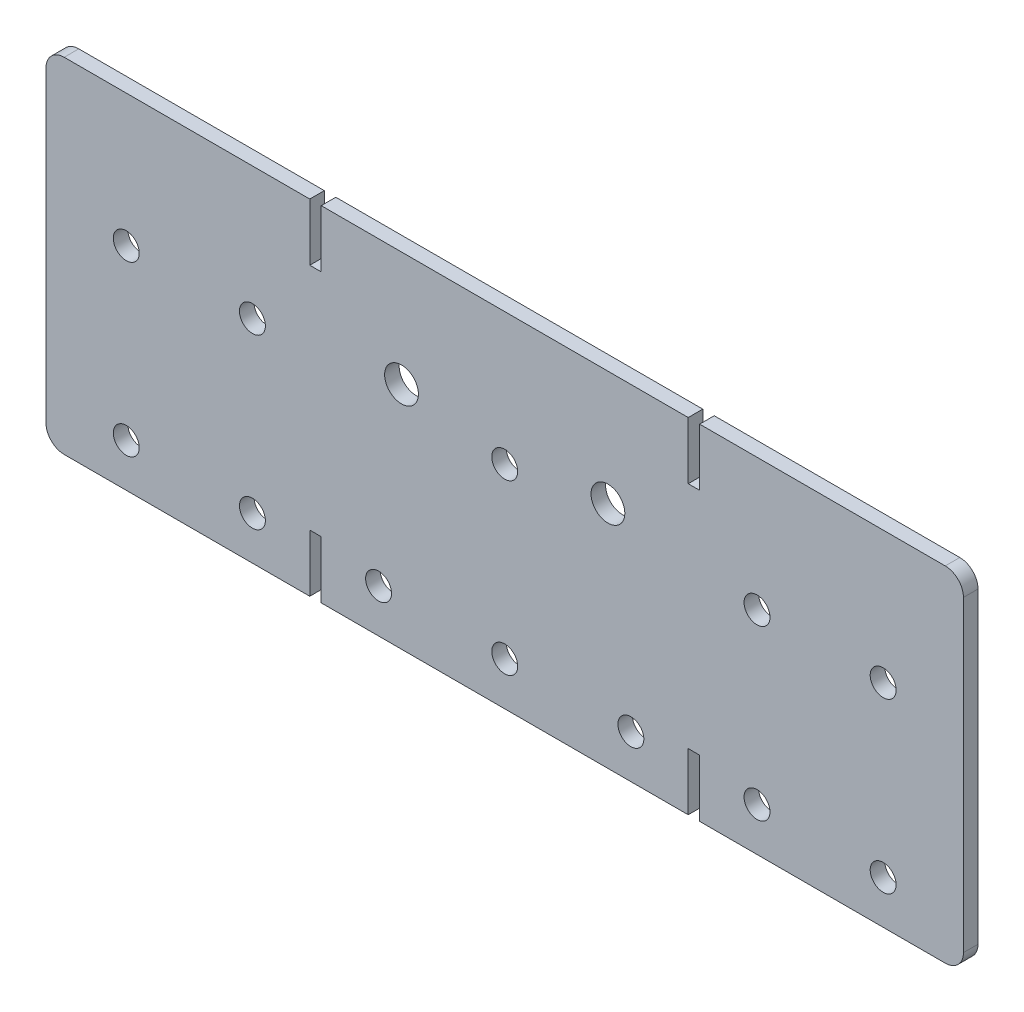
SolidWorks part; units mm, degrees
ref_plane "Front Plane" through (0, 0, 0) normal (0, 0, 1) x (1, 0, 0)
ref_plane "Top Plane" through (0, 0, 0) normal (0, 1, 0) x (1, 0, 0)
ref_plane "Right Plane" through (0, 0, 0) normal (1, 0, 0) x (0, 0, -1)
sketch "Sketch1" plane through (0, 0, 0) normal (0, 0, 1) x (1, 0, 0)
  line L0 (13, -14.7) -> (23, -14.7) construction
  line L1 (0, 0) -> (80, 0)
  line L2 (0, 0) -> (0, -30)
  line L3 (0, -30) -> (80, -30)
  line L4 (80, 0) -> (80, -30)
  line L5 (2, -2) -> (12, -2) construction
  line L6 (2, -2) -> (2, -14.7) construction
  line L7 (2, -14.7) -> (12, -14.7) construction
  line L8 (12, -2) -> (12, -14.7) construction
  line L9 (23, -2) -> (23, -14.7) construction
  line L10 (13, -2) -> (23, -2) construction
  line L11 (13, -2) -> (13, -14.7) construction
  line L12 (24, -14.7) -> (34, -14.7) construction
  line L13 (34, -2) -> (34, -14.7) construction
  line L14 (24, -2) -> (34, -2) construction
  line L15 (24, -2) -> (24, -14.7) construction
  line L16 (35, -14.7) -> (45, -14.7) construction
  line L17 (45, -2) -> (45, -14.7) construction
  line L18 (35, -2) -> (45, -2) construction
  line L19 (35, -2) -> (35, -14.7) construction
  line L20 (46, -14.7) -> (56, -14.7) construction
  line L21 (56, -2) -> (56, -14.7) construction
  line L22 (46, -2) -> (56, -2) construction
  line L23 (46, -2) -> (46, -14.7) construction
  line L24 (57, -14.7) -> (67, -14.7) construction
  line L25 (67, -2) -> (67, -14.7) construction
  line L26 (57, -2) -> (67, -2) construction
  line L27 (57, -2) -> (57, -14.7) construction
  line L28 (68, -14.7) -> (78, -14.7) construction
  line L29 (78, -2) -> (78, -14.7) construction
  line L30 (68, -2) -> (78, -2) construction
  line L31 (68, -2) -> (68, -14.7) construction
  line L32 (13, -29.4) -> (23, -29.4) construction
  line L33 (23, -16.7) -> (23, -29.4) construction
  line L34 (13, -16.7) -> (23, -16.7) construction
  line L35 (13, -16.7) -> (13, -29.4) construction
  line L36 (24, -29.4) -> (34, -29.4) construction
  line L37 (34, -16.7) -> (34, -29.4) construction
  line L38 (24, -16.7) -> (34, -16.7) construction
  line L39 (24, -16.7) -> (24, -29.4) construction
  line L40 (35, -29.4) -> (45, -29.4) construction
  line L41 (45, -16.7) -> (45, -29.4) construction
  line L42 (35, -16.7) -> (45, -16.7) construction
  line L43 (35, -16.7) -> (35, -29.4) construction
  line L44 (46, -29.4) -> (56, -29.4) construction
  line L45 (56, -16.7) -> (56, -29.4) construction
  line L46 (46, -16.7) -> (56, -16.7) construction
  line L47 (46, -16.7) -> (46, -29.4) construction
  line L48 (57, -29.4) -> (67, -29.4) construction
  line L49 (67, -16.7) -> (67, -29.4) construction
  line L50 (57, -16.7) -> (67, -16.7) construction
  line L51 (57, -16.7) -> (57, -29.4) construction
  line L52 (68, -29.4) -> (78, -29.4) construction
  line L53 (78, -16.7) -> (78, -29.4) construction
  line L54 (68, -16.7) -> (78, -16.7) construction
  line L55 (68, -16.7) -> (68, -29.4) construction
  line L56 (2, -29.4) -> (12, -29.4) construction
  line L57 (12, -16.7) -> (12, -29.4) construction
  line L58 (2, -16.7) -> (12, -16.7) construction
  line L59 (2, -16.7) -> (2, -29.4) construction
  line L60 (24, 0) -> (24, -5)
  line L61 (24, -5) -> (23, -5)
  line L62 (23, -5) -> (23, 0)
  line L63 (40, 0) -> (40, -30) construction
  line L64 (0, -15) -> (80, -15) construction
  line L65 (56, -5) -> (57, -5)
  line L66 (57, -5) -> (57, 0)
  line L67 (56, 0) -> (56, -5)
  line L68 (24, -25) -> (23, -25)
  line L69 (56, -25) -> (57, -25)
  line L70 (57, -25) -> (57, -30)
  line L71 (56, -30) -> (56, -25)
  line L72 (23, -25) -> (23, -30)
  line L73 (24, -30) -> (24, -25)
  circle A0 centre (7, -11.525) radius 1.1303
  circle A1 centre (31, -10) radius 1.4732
  circle A2 centre (49, -10) radius 1.4732
  circle A3 centre (18, -11.525) radius 1.1303
  circle A4 centre (29, -11.525) radius 1.1303 [skipped]
  circle A5 centre (40, -11.525) radius 1.1303
  circle A6 centre (51, -11.525) radius 1.1303 [skipped]
  circle A7 centre (62, -11.525) radius 1.1303
  circle A8 centre (73, -11.525) radius 1.1303
  circle A9 centre (18, -26.225) radius 1.1303
  circle A10 centre (29, -26.225) radius 1.1303
  circle A11 centre (40, -26.225) radius 1.1303
  circle A12 centre (51, -26.225) radius 1.1303
  circle A13 centre (62, -26.225) radius 1.1303
  circle A14 centre (73, -26.225) radius 1.1303
  circle A15 centre (7, -26.225) radius 1.1303
  circle A16 centre (31, -10) radius 2.3241 construction
  circle A17 centre (31, -10) radius 3.6571 construction
  point P11 (7, -14.7)
  dimension "D7" = 2.9464
  dimension "D11" = 2.2606
  dimension "D16" = 4.6482
  dimension "D1" = 3.175
  dimension "D2" = 12.7
  dimension "D3" = 10
  dimension "D4" = 2
  dimension "D5" = 2
  dimension "D6" = 18
  dimension "D8" = 80
  dimension "D9" = 31
  dimension "D10" = 10
  dimension "D14" = 2
  dimension "D15" = 2
  dimension "D17" = 30
  dimension "D18" = 5
  dimension "D12" = 7
  dimension "D13" = 2
extrude "Boss-Extrude1" add sketch "Sketch1" along normal blind 1.27 contours L73 L3 L71 L69 L70 L4 L1 L66 L65 L67 L60 L61 L62 L2 L72 L68 A15 A14 A13 A12 A11 A10 A9 A8 A7 A5 A3 A2 A1 A0
fillet "Fillet1" radius 1.5875 4 edges at (0, -30, 0.635) (0, 0, 0.635) (80, -30, 0.635) (80, 0, 0.635)
equation "\"D9@Sketch1\"=(\"D8@Sketch1\"-\"D6@Sketch1\")/2"
